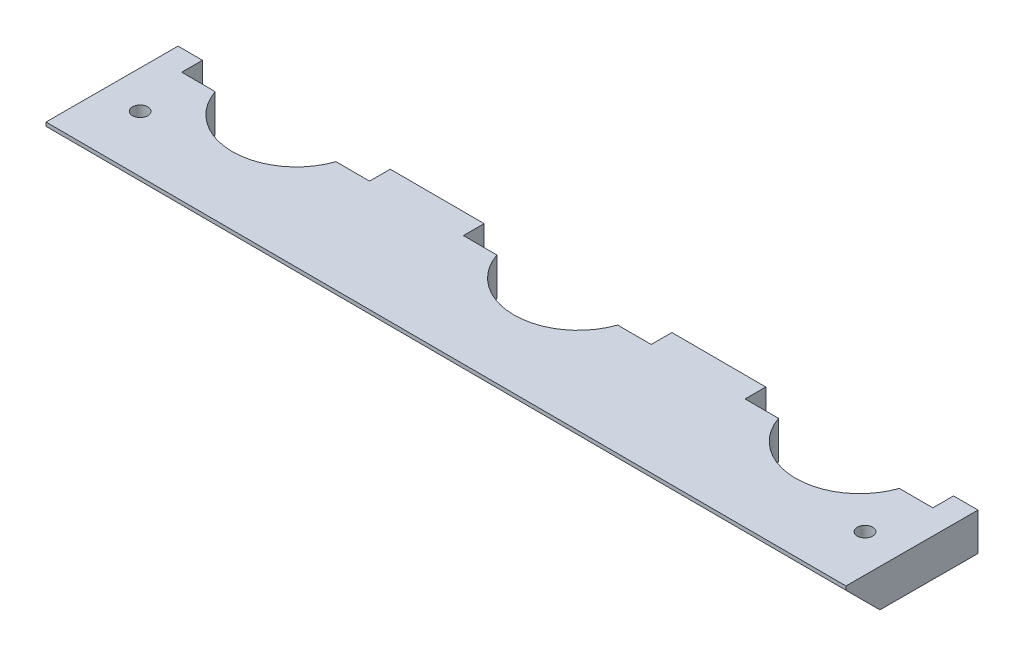
SolidWorks part; units mm, degrees
ref_plane "Płaszczyzna przednia" through (0, 0, 0) normal (0, 0, 1) x (1, 0, 0)
ref_plane "Płaszczyzna górna" through (0, 0, 0) normal (0, 1, 0) x (1, 0, 0)
ref_plane "Płaszczyzna prawa" through (0, 0, 0) normal (1, 0, 0) x (0, 0, -1)
sketch "Sketch2" plane through (0, 0, 0) normal (0, 1, 0) x (1, 0, 0)
  line L2 (-138.973, 39.1792) -> (-139.0522, 4.1793)
  line L3 (-139.0522, 4.1793) -> (73.9473, 3.6977)
  line L4 (74.027, 38.6976) -> (73.9473, 3.6977)
  line L5 (-107.4205, 62.3676) -> (-107.5199, 18.3936) construction
  line L7 (-132.4855, 33.6645) -> (-123.5712, 33.6443)
  line L9 (-132.4855, 33.6645) -> (-132.473, 39.1645)
  line L10 (-82.473, 39.0515) -> (-82.4855, 33.5515)
  line L11 (-138.973, 39.1792) -> (-132.473, 39.1645)
  line L12 (-57.4857, 33.4949) -> (-57.4732, 38.995)
  line L13 (-82.473, 39.0515) -> (-57.4732, 38.995)
  line L14 (-82.4855, 33.5515) -> (-91.3999, 33.5716)
  line L15 (-57.4857, 33.4949) -> (-48.5714, 33.4748)
  line L16 (-7.4857, 33.3819) -> (-16.4001, 33.402)
  line L17 (-7.4732, 38.8819) -> (-7.4857, 33.3819)
  line L18 (17.5141, 33.3253) -> (17.5266, 38.8254)
  line L19 (17.5141, 33.3253) -> (26.4284, 33.3052)
  line L20 (67.5141, 33.2123) -> (58.5997, 33.2325)
  line L21 (67.5266, 38.7123) -> (67.5141, 33.2123)
  line L22 (-7.4732, 38.8819) -> (17.5266, 38.8254)
  line L23 (67.5266, 38.7123) -> (74.027, 38.6976)
  arc A4 (-123.5712, 33.6443) -> (-91.3999, 33.5716) centre (-107.4731, 39.108) ccw
  arc A5 (-48.5714, 33.4748) -> (-16.4001, 33.402) centre (-32.4733, 38.9384) ccw
  arc A6 (26.4284, 33.3052) -> (58.5997, 33.2325) centre (42.5265, 38.7688) ccw
  point P4 (-104.1372, 39.0751)
  point P8 (-115.6371, 39.1103)
  point P12 (-95.973, 39.082)
  point P15 (-107.4702, 40.3806)
  dimension "D3" = 31.5
  dimension "D5" = 213
  dimension "D9" = 6.5
  dimension "D4" = 50.0001
  dimension "D14" = 34
  dimension "D11" = 17
  dimension "D1" = 213
  dimension "D2" = 35
  dimension "D6" = 360
  dimension "D7" = 13.5
  dimension "D8" = 213.0005
  dimension "D10" = 0
  dimension "D12" = 5.5
  dimension "D13" = 50
  dimension "D15" = 3
  dimension "D16" = 89.999
  dimension "D17" = 8.9143
extrude "Boss-Extrude3" add sketch "Sketch2" along normal blind 10
sketch "Sketch4" plane through (0.0879, 0, -38.8648) normal (0.0023, 0, -1) x (-1, 0, -0.0023)
  line L0 (62.5612, -12) -> (77.5612, -12)
  line L1 (62.5612, -12) -> (70.0612, -8.5) construction
  line L2 (57.5613, 0) -> (82.5611, 0) construction
  line L3 (77.5612, -12) -> (82.5611, 0)
  line L4 (62.5612, -12) -> (57.5613, 0)
  line L5 (77.5612, -12) -> (70.0612, -8.5) construction
  circle A0 centre (70.0612, -8.5) radius 1.5
  line M8 (57.5613, 0) -> (82.5611, 0)
  dimension "D3" = 3
  dimension "D1" = 15
  dimension "D2" = 12
  dimension "D4" = 3.5
extrude "Boss-Extrude4" add sketch "Sketch4" against normal blind 5 contours L4 L0 L3 A0 M8
ref_plane "Plane1" through (-77.561, 0, -0.1754) normal (1, 0, 0.0023) x (0.0023, 0, -1)
sketch "Sketch5" plane through (-77.561, 0, -0.1754) normal (1, 0, 0.0023) x (0.0023, 0, -1)
  line L0 (33.8649, -12) -> (26.8649, 0)
  line L5 (33.3649, 0) -> (33.8649, 0) construction
  point P4 (33.8649, -12)
rib "Rib6" sketch "Sketch5" sketch "Sketch5" thickness 2.5 parameters "D1"=2.5
ref_plane "Plane3" through (-70.061, 0, -0.1584) normal (1, 0, 0.0023) x (0.0023, 0, -1)
mirror "Mirror2" about plane through (-70.061, 0, -0.1584) normal (1, 0, 0.0023) of "Rib6"
chamfer "Chamfer2" distance 1 angle 45 1 edges at (-71.4844, -8.5, -34.0266)
pattern_linear "LPattern4" count 2 spacing 75 along (1, 0, 0.0023) of "Boss-Extrude4", "Rib6", "Mirror2", "Chamfer2"
chamfer "Chamfer3" distance 9 angle 45 1 edges at (-32.5524, 0, -3.9385)
sketch "Sketch8" plane through (0, 10, 0) normal (0, 1, 0) x (1, 0, 0)
  line L0 (-138.973, 39.1792) -> (-139.0182, 19.1792)
  line L1 (-139.0182, 19.1792) -> (-129.0182, 19.1566)
  line L2 (-138.973, 39.1792) -> (-139.0522, 4.1793) construction
  circle A0 centre (-129.0182, 19.1566) radius 2.05
  point P8 (0, 0)
  dimension "D3" = 4.1
  dimension "D1" = 20
  dimension "D2" = 10
extrude "Cut-Extrude1" cut sketch "Sketch8" against normal blind 4
sketch "Sketch9" plane through (0, 6, 0) normal (0, 1, 0) x (1, 0, 0)
  circle A0 centre (-129.0182, 19.1566) radius 1.6
  circle A2 centre (-129.0182, 19.1566) radius 2.05 construction
  dimension "D1" = 3.2
extrude "Cut-Extrude2" cut sketch "Sketch9" against normal blind 5
ref_plane "Plane4" through (-32.5612, 0, -0.0736) normal (-1, 0, -0.0023) x (-0.0023, 0, 1)
mirror "Mirror4" about plane through (-32.5612, 0, -0.0736) normal (-1, 0, -0.0023) of "Cut-Extrude2", "Cut-Extrude1"
